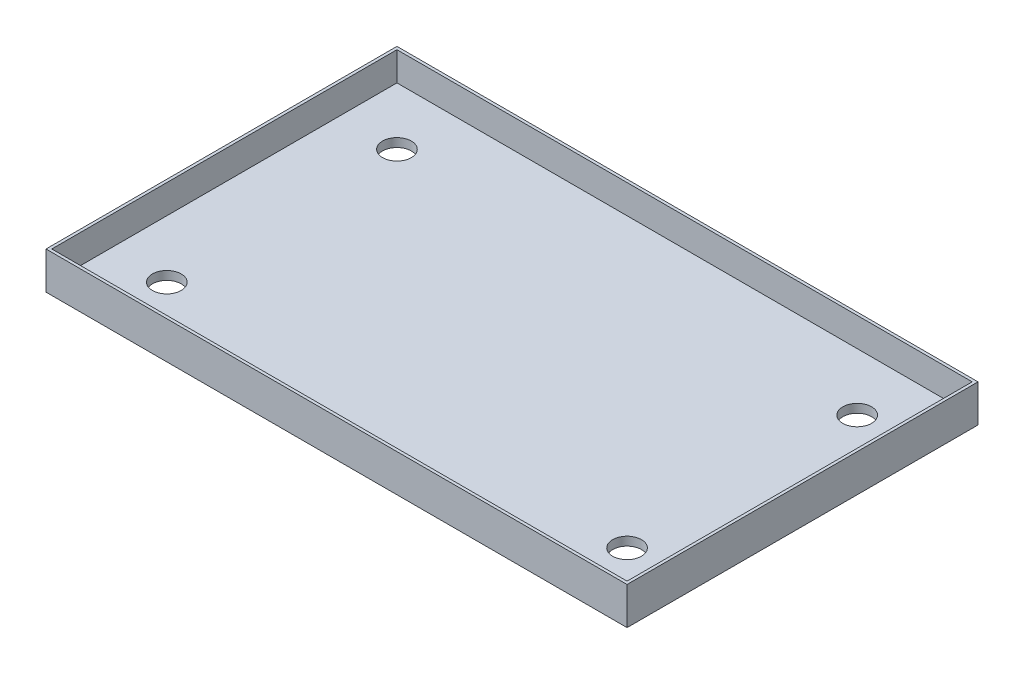
SolidWorks part; units mm, degrees
ref_plane "Front Plane" through (0, 0, 0) normal (0, 0, 1) x (1, 0, 0)
ref_plane "Top Plane" through (0, 0, 0) normal (0, 1, 0) x (1, 0, 0)
ref_plane "Right Plane" through (0, 0, 0) normal (1, 0, 0) x (0, 0, -1)
sketch "Sketch1" plane through (0, 0, 0) normal (0, 1, 0) x (1, 0, 0)
  line L0 (0, -55) -> (0, 55) construction
  line L1 (100, -60) -> (-100, -60)
  line L2 (100, -60) -> (100, 60)
  line L3 (100, 60) -> (-100, 60)
  line L4 (-100, -60) -> (-100, 60)
  line L5 (100, -60) -> (-100, 60) construction
  line L6 (100, 60) -> (-100, -60) construction
  line L7 (-55, 0) -> (55, 0) construction
  circle A0 centre (-80, 40) radius 5
  circle A1 centre (80, 40) radius 5
  circle A2 centre (80, -40) radius 5
  circle A3 centre (-80, -40) radius 5
  point P0 (0, 0)
  dimension "D3" = 10
  dimension "D1" = 200
  dimension "D2" = 120
  dimension "D4" = 20
  dimension "D5" = 20
extrude "Boss-Extrude3" add sketch "Sketch1" along normal mid plane 3
sketch "Sketch2" plane through (-100, 0, 0) normal (-1, 0, 0) x (0, 0, 1)
  line L0 (0, 17.261) -> (0, -11.6439) construction
  line L2 (-60, -1.5) -> (60, -1.5)
  line L3 (-60, -1.5) -> (-60, 11.5)
  line L4 (-60, 11.5) -> (60, 11.5)
  line L5 (60, -1.5) -> (60, 11.5)
  dimension "D1" = 120
  dimension "D2" = 13
extrude "Boss-Extrude4" add sketch "Sketch2" along normal blind 1
mirror "Mirror1" about plane through (0, 0, 0) normal (1, 0, 0) of "Boss-Extrude4"
sketch "Sketch3" plane through (0, 0, -60) normal (0, 0, -1) x (-1, 0, 0)
  line L5 (-101, -1.5) -> (101, -1.5)
  line L6 (-101, -1.5) -> (-101, 11.5)
  line L7 (-101, 11.5) -> (101, 11.5)
  line L8 (101, -1.5) -> (101, 11.5)
extrude "Boss-Extrude6" add sketch "Sketch3" along normal blind 1
mirror "Mirror2" about plane through (0, 0, 0) normal (0, 0, 1) of "Boss-Extrude6"
